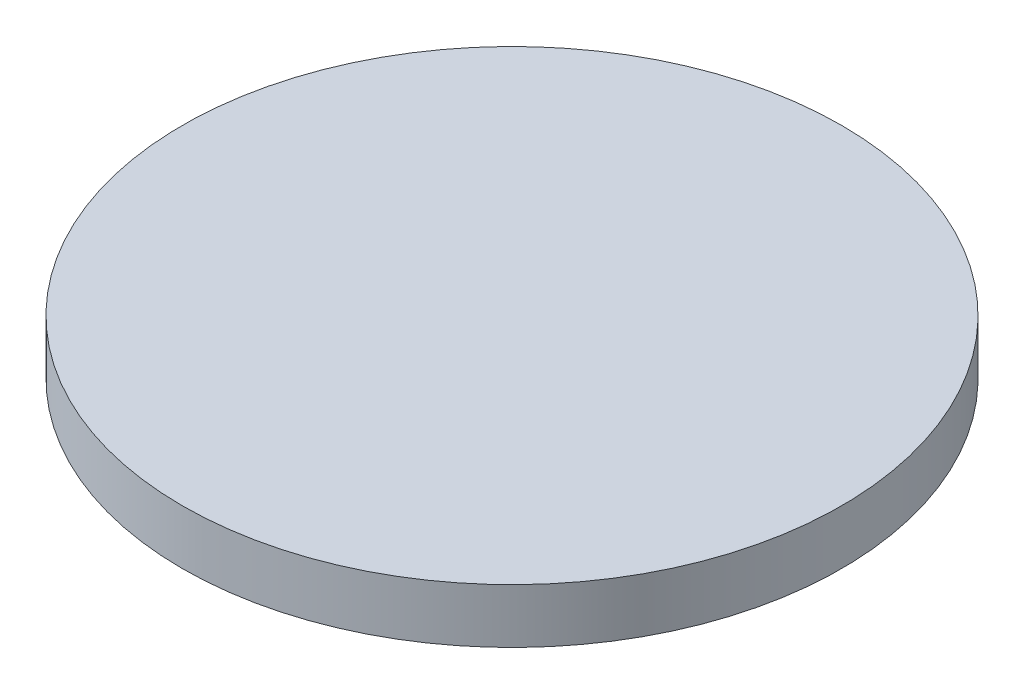
SolidWorks part; units mm, degrees
ref_plane "Front Plane" through (0, 0, 0) normal (0, 0, 1) x (1, 0, 0)
ref_plane "Top Plane" through (0, 0, 0) normal (0, 1, 0) x (1, 0, 0)
ref_plane "Right Plane" through (0, 0, 0) normal (1, 0, 0) x (0, 0, -1)
sketch "Sketch1" plane through (0, 0, 0) normal (0, 1, 0) x (1, 0, 0)
  circle A0 centre (0, 0) radius 10.9
  dimension "D1" = 21.8
extrude "Boss-Extrude1" add sketch "Sketch1" along normal blind 1.8
